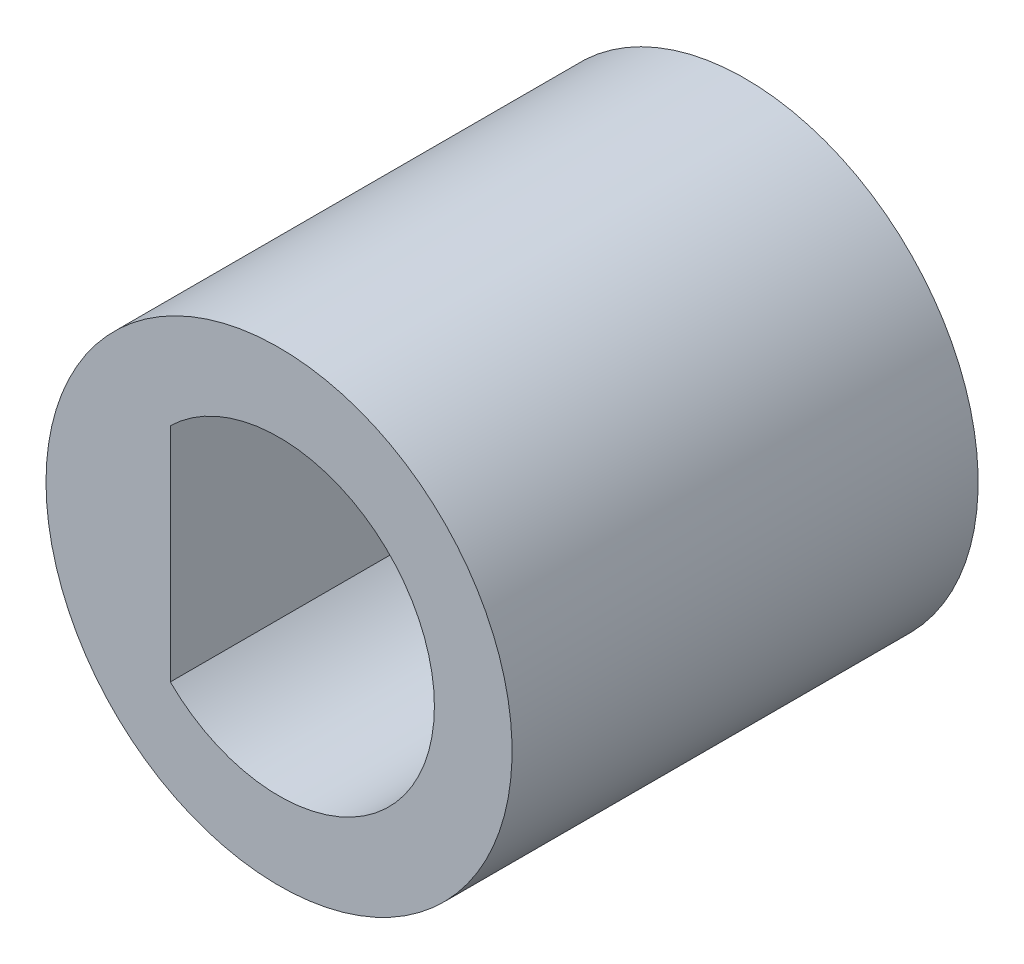
SolidWorks part; units mm, degrees
ref_plane "Front Plane" through (0, 0, 0) normal (0, 0, 1) x (1, 0, 0)
ref_plane "Top Plane" through (0, 0, 0) normal (0, 1, 0) x (1, 0, 0)
ref_plane "Right Plane" through (0, 0, 0) normal (1, 0, 0) x (0, 0, -1)
sketch "Sketch1" plane through (0, 0, 0) normal (0, 0, 1) x (1, 0, 0)
  line L0 (-2.2225, -2.2674) -> (-2.2225, 2.2674)
  circle A0 centre (0, 0) radius 4.7625
  arc A1 (-2.2225, -2.2674) -> (-2.2225, 2.2674) centre (0, 0) ccw
  dimension "D1" = 9.525
  dimension "D2" = 6.35
  dimension "D3" = 2.2225
extrude "Boss-Extrude1" add sketch "Sketch1" along normal blind 9.525
